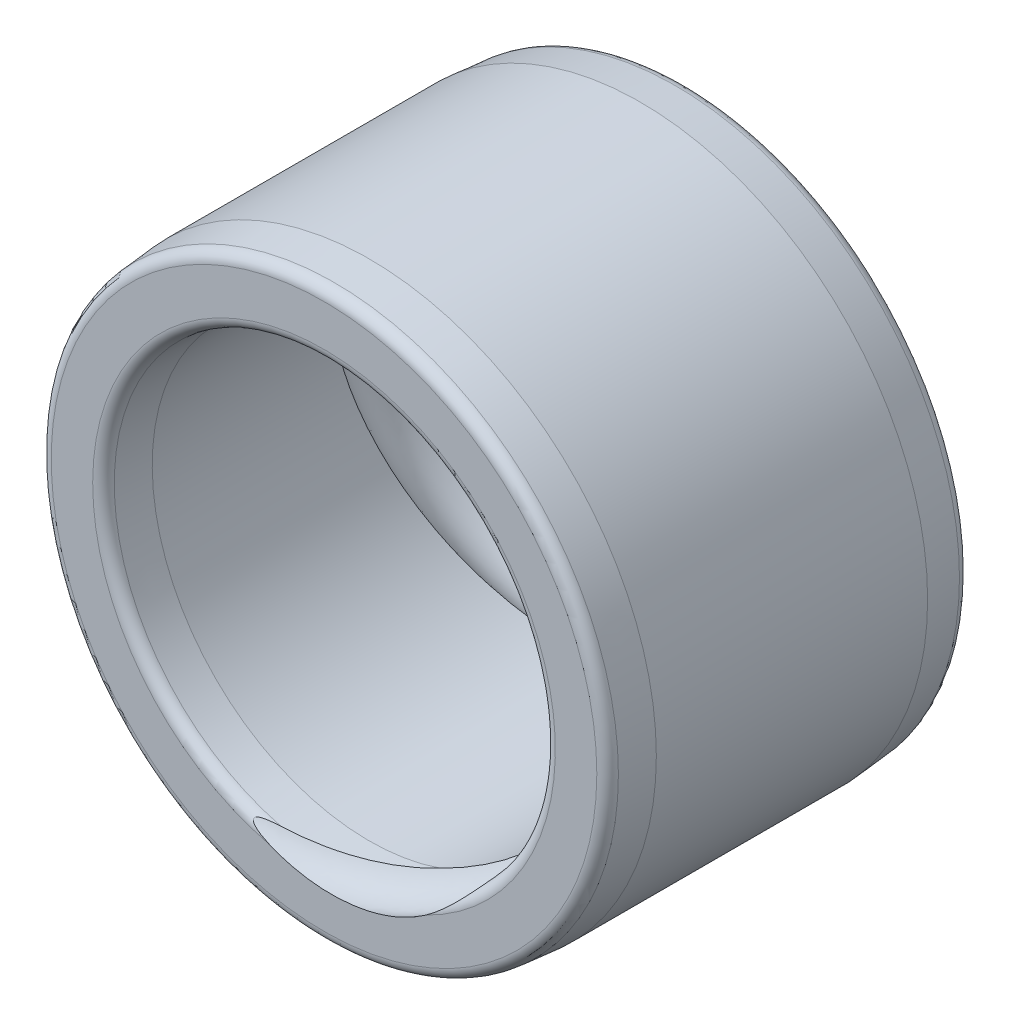
SolidWorks part; units mm, degrees
material "Phosphor bronze 10% D, UNS C52400"
ref_plane "Front Plane" through (0, 0, 0) normal (0, 0, 1) x (1, 0, 0)
ref_plane "Top Plane" through (0, 0, 0) normal (0, 1, 0) x (1, 0, 0)
ref_plane "Right Plane" through (0, 0, 0) normal (1, 0, 0) x (0, 0, -1)
sketch "Sketch1" plane through (0, 0, 0) normal (1, 0, 0) x (0, 0, -1)
  line L0 (0, 10.2331) -> (0, 12.0669)
  line L1 (0.4564, 12.565) -> (2, 12.7)
  line L2 (2, 12.7) -> (14, 12.7)
  line L3 (14, 12.7) -> (15.5436, 12.565)
  line L4 (16, 12.0669) -> (16, 10.2331)
  line L5 (15.5436, 9.735) -> (14, 9.6)
  line L6 (14, 9.6) -> (2, 9.6)
  line L7 (2, 9.6) -> (0.4564, 9.735)
  line L8 (0, 0) -> (16, 0) construction
  arc A0 (16, 10.2331) -> (15.5436, 9.735) centre (15.5, 10.2331) cw
  arc A1 (16, 12.0669) -> (15.5436, 12.565) centre (15.5, 12.0669) ccw
  arc A2 (0.4564, 9.735) -> (0, 10.2331) centre (0.5, 10.2331) cw
  arc A3 (0, 12.0669) -> (0.4564, 12.565) centre (0.5, 12.0669) cw
  point P17 (0, 9.775)
  point P20 (0, 12.525)
  dimension "D12" = 0.5
  dimension "D1" = 2
  dimension "D2" = 9.6
  dimension "D3" = 2
  dimension "D4" = 5
  dimension "D5" = 5
  dimension "D6" = 2
  dimension "D7" = 5
  dimension "D8" = 5
  dimension "D9" = 2
  dimension "D10" = 16
  dimension "D11" = 12.7
revolve "Revolve1" add sketch "Sketch1" angle 360 about L8
ref_plane "Plane1" through (0, 0, 2.5) normal (0, 0, 1) x (1, 0, 0)
sketch "Sketch18" plane through (0, 0, 2.5) normal (0, 0, 1) x (1, 0, 0)
  circle A0 centre (0, 0) radius 9
  dimension "D1" = 9
curve "Helix/Spiral2" pitch 16 height 20 turns 1.25
sweep "Cut-Sweep2" cut path "Helix/Spiral2" circular profile diameter 3 parameters "D3"=3
